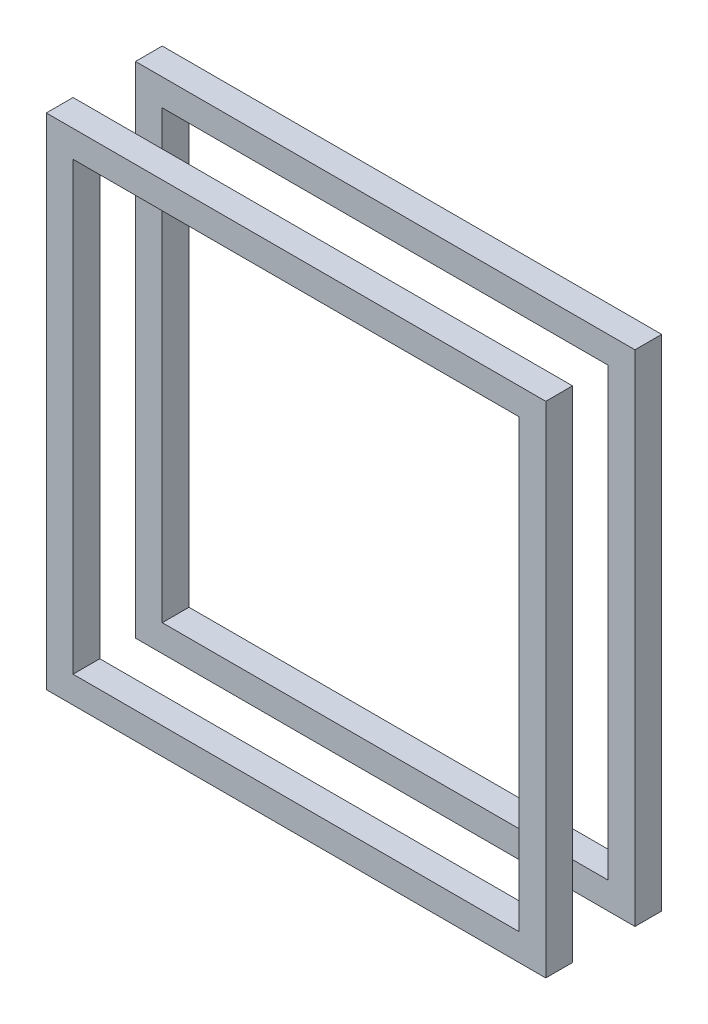
SolidWorks part; units mm, degrees
ref_plane "Front Plane" through (0, 0, 0) normal (0, 0, 1) x (1, 0, 0)
ref_plane "Top Plane" through (0, 0, 0) normal (0, 1, 0) x (1, 0, 0)
ref_plane "Right Plane" through (0, 0, 0) normal (1, 0, 0) x (0, 0, -1)
sketch "Sketch1" plane through (0, 0, 0) normal (0, 0, 1) x (1, 0, 0)
  line L0 (-28, -28) -> (-28, 28)
  line L1 (-25, -25) -> (25, -25)
  line L2 (-25, -25) -> (-25, 25)
  line L3 (-25, 25) -> (25, 25)
  line L4 (25, -25) -> (25, 25)
  line L5 (-25, -25) -> (25, 25) construction
  line L6 (-25, 25) -> (25, -25) construction
  line L7 (-28, 28) -> (28, 28)
  line L8 (28, -28) -> (28, 28)
  line L9 (-28, -28) -> (28, -28)
  point P0 (0, 0)
  dimension "D1" = 50
  dimension "D2" = 50
  dimension "D3" = 3
extrude "Boss-Extrude1" add sketch "Sketch1" along normal blind 3 contours L3 L4 L1 L2 | L7 L8 L9 L0
ref_plane "Plane4" through (0, 0, -10) normal (0, 0, 1) x (1, 0, 0)
sketch "Sketch2" plane through (0, 0, -10) normal (0, 0, 1) x (1, 0, 0)
  line L0 (-28, -28) -> (-28, 28)
  line L1 (-25, -25) -> (25, -25)
  line L2 (-25, -25) -> (-25, 25)
  line L3 (-25, 25) -> (25, 25)
  line L4 (25, -25) -> (25, 25)
  line L5 (-25, -25) -> (25, 25) construction
  line L6 (-25, 25) -> (25, -25) construction
  line L7 (-28, 28) -> (28, 28)
  line L8 (28, -28) -> (28, 28)
  line L9 (-28, -28) -> (28, -28)
  point P0 (0, 0)
  dimension "D1" = 50
  dimension "D2" = 50
  dimension "D3" = 3
extrude "Boss-Extrude2" add sketch "Sketch2" along normal blind 3 separate body
